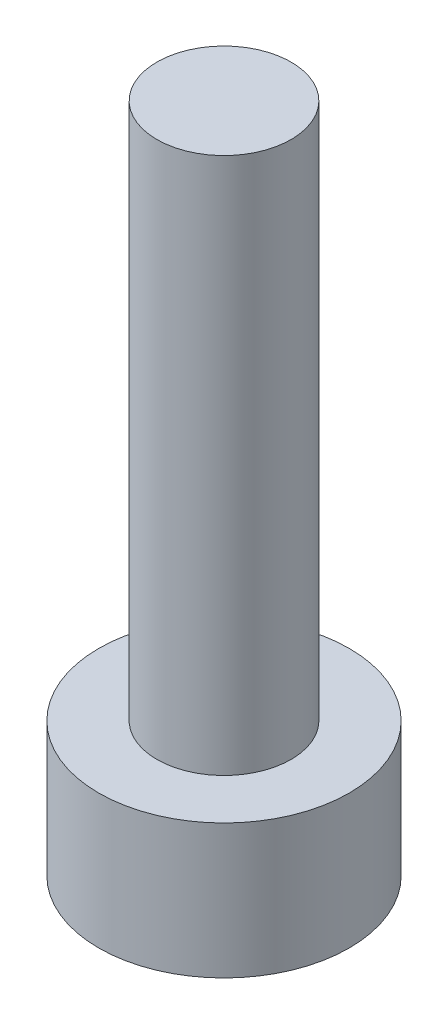
SolidWorks part; units mm, degrees
ref_plane "前视基准面" through (0, 0, 0) normal (0, 0, 1) x (1, 0, 0)
ref_plane "上视基准面" through (0, 0, 0) normal (0, 1, 0) x (1, 0, 0)
ref_plane "右视基准面" through (0, 0, 0) normal (1, 0, 0) x (0, 0, -1)
other "Configuration Table"
sketch "草图1" plane through (0, 0, 0) normal (0, 1, 0) x (1, 0, 0)
  circle A0 centre (0, 0) radius 2.8
  dimension "D1" = 5.6
extrude "凸台-拉伸1" add sketch "草图1" along normal blind 3
sketch "草图2" plane through (0, 3, 0) normal (0, 1, 0) x (1, 0, 0)
  circle A0 centre (0, 0) radius 1.5
  dimension "D1" = 3
extrude "凸台-拉伸2" add sketch "草图2" along normal blind 12
cosmetic thread "装饰螺纹线1" parameters "D2"=2
sketch "草图3" plane through (0, 0, 0) normal (0, -1, 0) x (1, 0, 0)
  line L1 (1.0846, -0.9524) -> (1.3671, 0.4631)
  line L2 (1.3671, 0.4631) -> (0.2825, 1.4155)
  line L3 (0.2825, 1.4155) -> (-1.0846, 0.9524)
  line L4 (-1.0846, 0.9524) -> (-1.3671, -0.4631)
  line L5 (-1.3671, -0.4631) -> (-0.2825, -1.4155)
  line L6 (-0.2825, -1.4155) -> (1.0846, -0.9524)
  circle A0 centre (0, 0) radius 1.25 construction
  dimension "D1" = 2.5
extrude "切除-拉伸1" cut sketch "草图3" against normal blind 1.5
